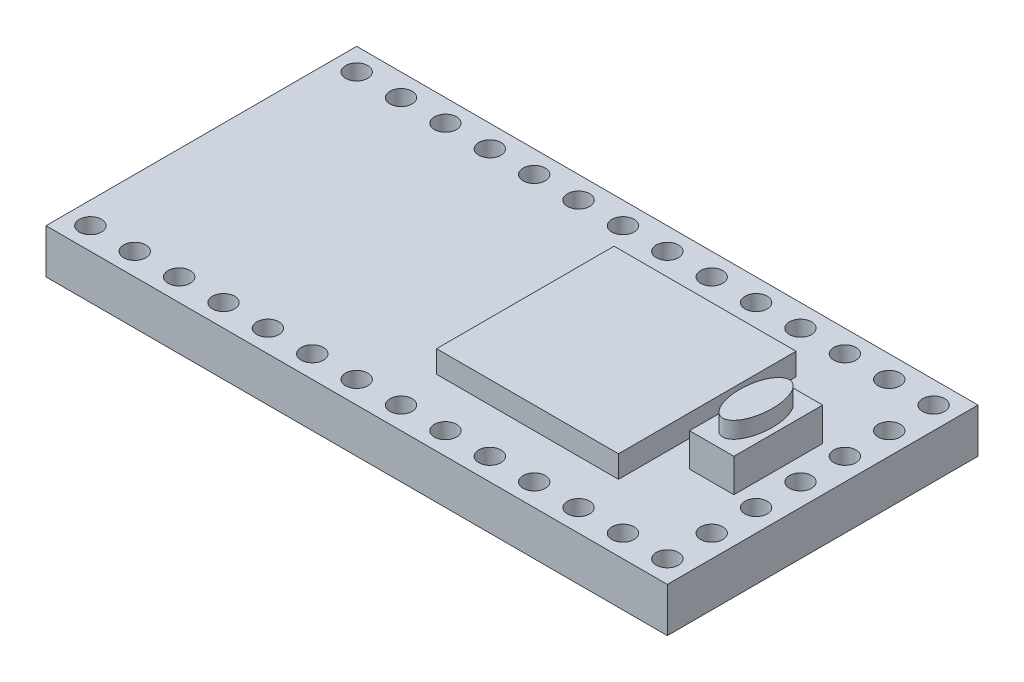
SolidWorks part; units mm, degrees
ref_plane "Front Plane" through (0, 0, 0) normal (0, 0, 1) x (1, 0, 0)
ref_plane "Top Plane" through (0, 0, 0) normal (0, 1, 0) x (1, 0, 0)
ref_plane "Right Plane" through (0, 0, 0) normal (1, 0, 0) x (0, 0, -1)
sketch "Sketch1" plane through (0, 0, 0) normal (0, 1, 0) x (1, 0, 0)
  line L1 (-17.78, 8.89) -> (17.78, 8.89)
  line L2 (-17.78, 8.89) -> (-17.78, -8.89)
  line L3 (-17.78, -8.89) -> (17.78, -8.89)
  line L4 (17.78, 8.89) -> (17.78, -8.89)
  line L5 (-17.78, 8.89) -> (17.78, -8.89) construction
  line L6 (-17.78, -8.89) -> (17.78, 8.89) construction
  point P0 (0, 0)
  dimension "D1" = 35.56
  dimension "D2" = 17.78
extrude "Boss-Extrude1" add sketch "Sketch1" along normal blind 2.54
sketch "Sketch2" plane through (0, 2.54, 0) normal (0, 1, 0) x (1, 0, 0)
  line L0 (17.78, 8.89) -> (-17.78, 8.89) construction
  line L1 (-17.78, 8.89) -> (-17.78, -8.89) construction
  line L2 (-23.8222, 0) -> (21.6649, 0) construction
  circle A0 centre (-16.51, 7.62) radius 0.635
  circle A1 centre (-16.51, -7.62) radius 0.635
  circle A2 centre (-13.97, 7.62) radius 0.635
  circle A3 centre (-13.97, -7.62) radius 0.635
  circle A4 centre (-11.43, 7.62) radius 0.635
  circle A5 centre (-11.43, -7.62) radius 0.635
  circle A6 centre (-8.89, 7.62) radius 0.635
  circle A7 centre (-8.89, -7.62) radius 0.635
  circle A8 centre (-6.35, 7.62) radius 0.635
  circle A9 centre (-6.35, -7.62) radius 0.635
  circle A10 centre (-3.81, 7.62) radius 0.635
  circle A11 centre (-3.81, -7.62) radius 0.635
  circle A12 centre (-1.27, 7.62) radius 0.635
  circle A13 centre (-1.27, -7.62) radius 0.635
  circle A14 centre (1.27, 7.62) radius 0.635
  circle A15 centre (1.27, -7.62) radius 0.635
  circle A16 centre (3.81, 7.62) radius 0.635
  circle A17 centre (3.81, -7.62) radius 0.635
  circle A18 centre (6.35, 7.62) radius 0.635
  circle A19 centre (6.35, -7.62) radius 0.635
  circle A20 centre (8.89, 7.62) radius 0.635
  circle A21 centre (8.89, -7.62) radius 0.635
  circle A22 centre (11.43, 7.62) radius 0.635
  circle A23 centre (11.43, -7.62) radius 0.635
  circle A24 centre (13.97, 7.62) radius 0.635
  circle A25 centre (13.97, -7.62) radius 0.635
  circle A26 centre (16.51, 7.62) radius 0.635
  circle A27 centre (16.51, -7.62) radius 0.635
  circle A28 centre (16.51, 5.08) radius 0.635
  circle A29 centre (16.51, 2.54) radius 0.635
  circle A30 centre (16.51, 0) radius 0.635
  circle A31 centre (16.51, -2.54) radius 0.635
  circle A32 centre (16.51, -5.08) radius 0.635
  dimension "D1" = 1.27
  dimension "D2" = 1.27
  dimension "D3" = 1.27
  dimension "D4" = 14
  dimension "D5" = 6
extrude "Cut-Extrude1" cut sketch "Sketch2" against normal up to next (2.54 mm away)
sketch "Sketch3" plane through (0, 2.54, 0) normal (0, 1, 0) x (1, 0, 0)
  line L0 (17.78, -8.89) -> (17.78, 8.89) construction
  line L1 (15.24, 2.54) -> (12.7, 2.54)
  line L2 (15.24, 2.54) -> (15.24, -2.54)
  line L3 (15.24, -2.54) -> (12.7, -2.54)
  line L4 (12.7, 2.54) -> (12.7, -2.54)
  line L5 (19.2082, 0) -> (9.5106, 0) construction
  point P9 (15.24, 0)
  dimension "D1" = 2.54
  dimension "D2" = 2.54
  dimension "D3" = 5.08
extrude "Boss-Extrude2" add sketch "Sketch3" along normal blind 1.905
sketch "Sketch4" plane through (0, 4.445, 0) normal (0, 1, 0) x (1, 0, 0)
  line L0 (15.24, -2.54) -> (15.24, 2.54) construction
  line L1 (12.7, -2.54) -> (15.24, -2.54) construction
  ellipse E0 centre (13.97, 0) end of major axis (13.97, -1.905) minor radius 0.9398
  point P8 (15.24, 0)
  point P11 (13.97, -2.54)
extrude "Boss-Extrude3" add sketch "Sketch4" along normal blind 0.9398
sketch "Sketch5" plane through (0, 2.54, 0) normal (0, 1, 0) x (1, 0, 0)
  line L0 (12.7, 2.54) -> (12.7, -2.54) construction
  line L1 (0.7616, 5.08) -> (11.176, 5.08)
  line L2 (0.7616, 5.08) -> (0.7616, -5.08)
  line L3 (0.7616, -5.08) -> (11.176, -5.08)
  line L4 (11.176, 5.08) -> (11.176, -5.08)
  line L5 (0.7616, 5.08) -> (11.176, -5.08) construction
  line L6 (0.7616, -5.08) -> (11.176, 5.08) construction
  point P0 (5.9688, 0)
  point P5 (12.7, 0)
  dimension "D1" = 10.16
  dimension "D2" = 1.524
  dimension "D3" = 6.7312
extrude "Boss-Extrude4" add sketch "Sketch5" along normal blind 1.27
